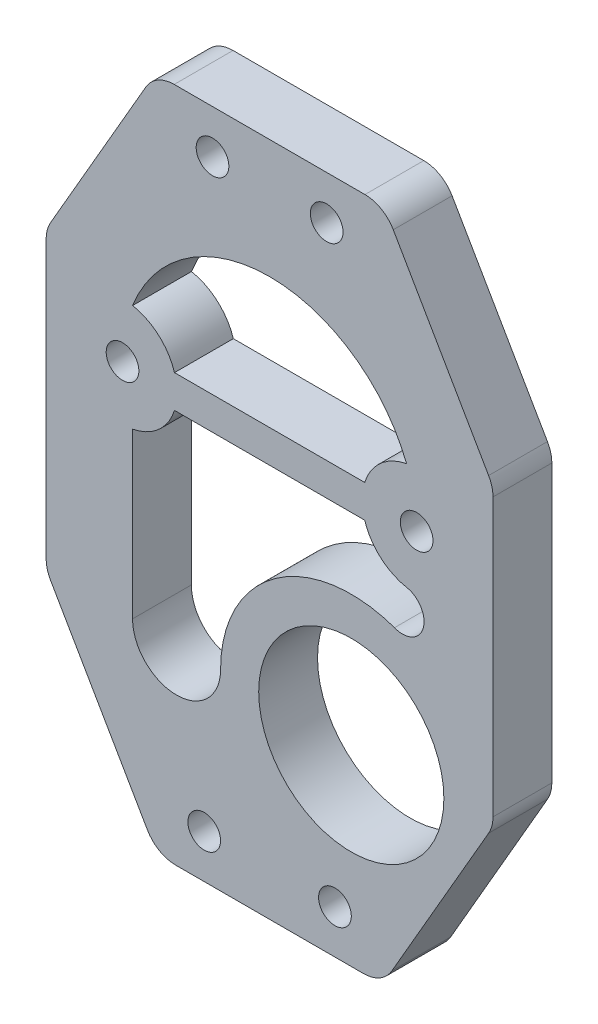
SolidWorks part; units mm, degrees
ref_plane "Front Plane" through (0, 0, 0) normal (0, 0, 1) x (1, 0, 0)
ref_plane "Top Plane" through (0, 0, 0) normal (0, 1, 0) x (1, 0, 0)
ref_plane "Right Plane" through (0, 0, 0) normal (1, 0, 0) x (0, 0, -1)
sketch "Sketch1" plane through (0, 0, 0) normal (0, 0, 1) x (1, 0, 0)
  line L0 (0, 34.1829) -> (0, -31) construction
  line L1 (-10.4877, 31) -> (10.4877, 31)
  line L2 (10.4877, 31) -> (20.1081, 14.337)
  line L3 (20.51, 12.837) -> (20.51, -12.5962)
  line L4 (20.1081, -14.0962) -> (10.3486, -31)
  line L5 (10.3486, -31) -> (-10.3486, -31)
  line L6 (-10.3486, -31) -> (-20.1081, -14.0962)
  line L7 (-20.51, -12.5962) -> (-20.51, 12.837)
  line L8 (-20.1081, 14.337) -> (-10.4877, 31)
  line L9 (-28.5813, 0) -> (26.9329, 0) construction
  line L10 (-12.58, -13.4) -> (-12.58, 1.6854)
  line L11 (-8.7303, 5.1) -> (8.7299, 5.1)
  line L12 (-8.7303, 8.1) -> (8.7299, 8.1)
  circle A0 centre (-5.24, 27) radius 1.5
  circle A1 centre (5.24, 27) radius 1.5
  circle A2 centre (-6, -27) radius 1.5
  circle A3 centre (6, -27) radius 1.5
  circle A4 centre (-13.5, 6.6) radius 1.5
  circle A5 centre (13.5, 6.6) radius 1.5
  circle A6 centre (7.5, -13.4) radius 8.5
  arc A7 (11.6226, -2.1304) -> (-4.5, -13.4) centre (7.5, -13.4) ccw
  arc A8 (11.4699, -2.0757) -> (12.5746, 1.686) centre (12.21, -0.25) ccw
  arc A9 (-12.58, -13.4) -> (-4.5, -13.4) centre (-8.54, -13.4) ccw
  arc A10 (-12.58, 1.6854) -> (-8.7303, 5.1) centre (-13.5, 6.6) ccw
  arc A11 (12.5739, 11.5139) -> (8.7299, 8.1) centre (13.5, 6.6) ccw
  arc A13 (12.5739, 11.5139) -> (-12.5741, 11.5135) centre (0, 6.6) ccw
  arc A14 (8.7299, 5.1) -> (12.5746, 1.686) centre (13.5, 6.6) ccw
  arc A15 (-8.7303, 8.1) -> (-12.5741, 11.5135) centre (-13.5, 6.6) ccw
  arc A16 (-20.1081, -14.0962) -> (-20.51, -12.5962) centre (-17.51, -12.5962) cw
  arc A17 (20.51, -12.5962) -> (20.1081, -14.0962) centre (17.51, -12.5962) cw
  arc A18 (20.1081, 14.337) -> (20.51, 12.837) centre (17.51, 12.837) cw
  arc A19 (-20.51, 12.837) -> (-20.1081, 14.337) centre (-17.51, 12.837) cw
  point P31 (0, 31)
  point P50 (20.51, -13.4)
  point P53 (20.51, 13.6408)
  point P56 (-20.51, 13.6408)
  dimension "D4" = 3
  dimension "D8" = 20.4
  dimension "D9" = 27
  dimension "D10" = 7.93
  dimension "D13" = 17
  dimension "D14" = 24
  dimension "D17" = 3.94
  dimension "D23" = 8.08
  dimension "D24" = 10
  dimension "D25" = 1.5
  dimension "D22" = 3
  dimension "D2" = 31
  dimension "D3" = 10.48
  dimension "D5" = 4
  dimension "D6" = 12
  dimension "D7" = 4
  dimension "D11" = 7.5
  dimension "D12" = 17.6
  dimension "D15" = 13.15
  dimension "D16" = 4.71
  dimension "D18" = 120
  dimension "D19" = 120
  dimension "D20" = 120
  dimension "D21" = 62
  dimension "D26" = 1.5
extrude "Boss-Extrude1" add sketch "Sketch1" along normal mid plane 5.4 contours A19 L7 A16 L6 L5 L4 A17 L3 A18 L2 L1 L8 A6 A5 A4 A3 A2 A1 A0 L11 A14 A8 A7 A9 L10 A10 L12 A15 A13 A11
fillet "Fillet1" radius 3 4 edges at (-10.3486, -31, 0) (10.3486, -31, 0) (10.4877, 31, 0) (-10.4877, 31, 0)
scale "Scale1" scale about centroid uniform scaling yes scale factor 1.9
